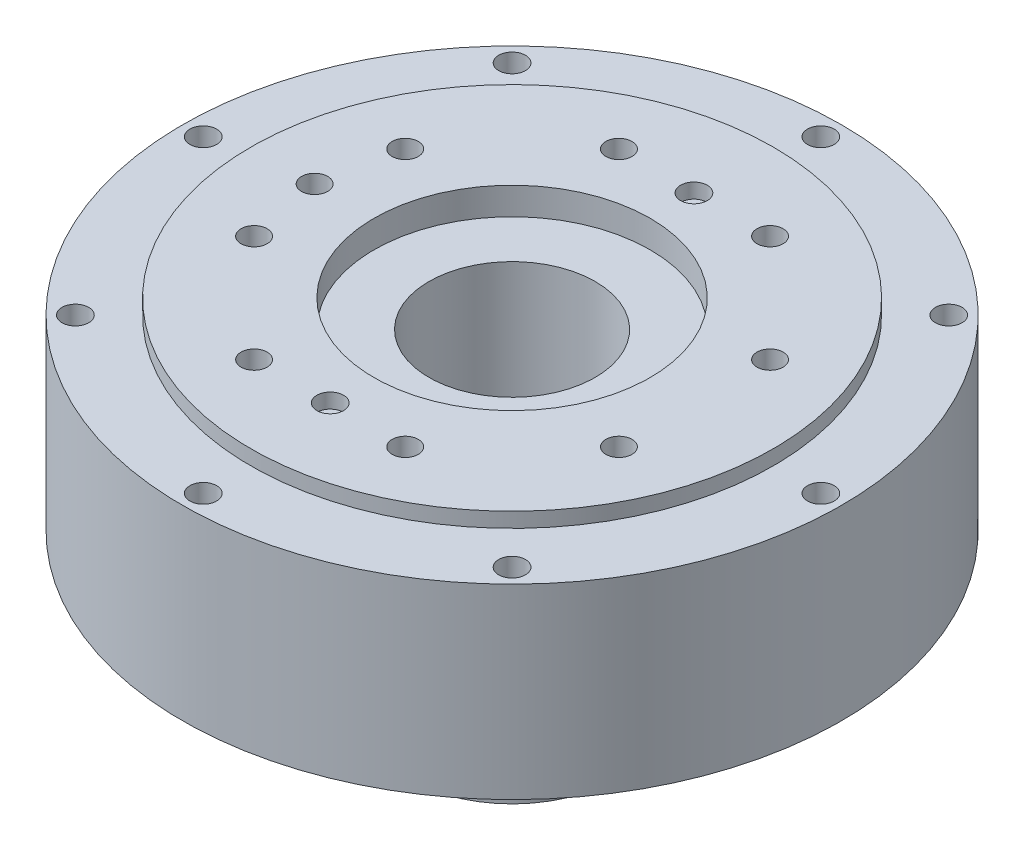
SolidWorks part; units mm, degrees
ref_plane "Front Plane" through (0, 0, 0) normal (0, 0, 1) x (1, 0, 0)
ref_plane "Top Plane" through (0, 0, 0) normal (0, 1, 0) x (1, 0, 0)
ref_plane "Right Plane" through (0, 0, 0) normal (1, 0, 0) x (0, 0, -1)
sketch "Sketch1" plane through (0, 0, 0) normal (1, 0, 0) x (0, 0, -1)
  line L4 (-28, 0) -> (-35, 0)
  line L5 (-35, 0) -> (-35, 34)
  line L12 (-35, 34) -> (-39.3, 34)
  line L13 (-39.3, 34) -> (-39.3, 44)
  line L14 (-39.3, 44) -> (-84.5, 44)
  line L15 (-84.5, 44) -> (-84.5, 55)
  line L20 (-84.5, 55) -> (-95, 55)
  line L23 (-111, 55) -> (-111, 117.85)
  line L24 (-111, 117.85) -> (-88, 117.85)
  line L25 (-88, 117.85) -> (-88, 122.85)
  line L26 (-88, 122.85) -> (-46.5, 122.85)
  line L28 (0, 0) -> (0, 248.8585) construction
  line L29 (-46.5, 122.85) -> (-46.5, 113.65)
  line L30 (-46.5, 113.65) -> (-28, 113.65)
  line L31 (0, 0) -> (-28, 0) construction
  line L32 (-28, 113.65) -> (-28, 0)
  line L33 (-98, 55) -> (-97.5, 57)
  line L34 (-97.5, 57) -> (-95.5, 57)
  line L35 (-95.5, 57) -> (-95, 55)
  line L36 (-96.5, 57) -> (-96.5, 55) construction
  line L37 (-95, 55) -> (-96.5, 56) construction
  line L38 (-96.5, 56) -> (-98, 55) construction
  line L39 (-98, 55) -> (-111, 55)
  dimension "D2" = 2
  dimension "D3" = 70
  dimension "D4" = 44
  dimension "D5" = 169
  dimension "D6" = 93
  dimension "D7" = 9.2
  dimension "D8" = 222
  dimension "D9" = 3
  dimension "D10" = 176
  dimension "D11" = 2
  dimension "D12" = 5
  dimension "D13" = 62.85
  dimension "D14" = 11
  dimension "D15" = 78.6
  dimension "D16" = 34
  dimension "D17" = 190
  dimension "D18" = 56
revolve "Revolve1" add sketch "Sketch1" angle 360 about L28
sketch "Sketch2" plane through (0, 117.85, 0) normal (0, 1, 0) x (1, 0, 0)
  line L0 (0, 0) -> (-178.8301, 0) construction
  circle A0 centre (0, 0) radius 104 construction
  circle A1 centre (-104, 0) radius 4.5
  circle A9 centre (-73.5391, 73.5391) radius 4.5
  circle A10 centre (0, 104) radius 4.5
  circle A11 centre (73.5391, 73.5391) radius 4.5
  circle A12 centre (104, 0) radius 4.5
  circle A13 centre (73.5391, -73.5391) radius 4.5
  circle A14 centre (0, -104) radius 4.5
  circle A15 centre (-73.5391, -73.5391) radius 4.5
  point P23 (0, 0)
  dimension "D1" = 9
  dimension "D4" = 208
  dimension "D2" = 8
extrude "Cut-Extrude1" cut sketch "Sketch2" against normal through all
sketch "Sketch4" plane through (0, 122.85, 0) normal (0, 1, 0) x (1, 0, 0)
  line L0 (0, 0) -> (-172.1172, 0) construction
  line L1 (0, 0) -> (-66.5, 0) construction
  line L2 (0, 0) -> (-61.438, 25.4484) construction
  circle A0 centre (0, 0) radius 66.5 construction
  circle A1 centre (-66.5, 0) radius 4.4
  circle A2 centre (-61.438, 25.4484) radius 4.4
  circle A4 centre (-25.4484, 61.438) radius 4.4
  circle A6 centre (25.4484, 61.438) radius 4.4
  circle A8 centre (61.438, 25.4484) radius 4.4
  circle A10 centre (61.438, -25.4484) radius 4.4
  circle A12 centre (25.4484, -61.438) radius 4.4
  circle A14 centre (-25.4484, -61.438) radius 4.4
  circle A16 centre (-61.438, -25.4484) radius 4.4
  circle A17 centre (-47.0226, 47.0226) radius 4.4 [skipped]
  circle A18 centre (-47.0226, -47.0226) radius 4.4 [skipped]
  circle A19 centre (0, -66.5) radius 4.4 [skipped]
  circle A20 centre (47.0226, -47.0226) radius 4.4 [skipped]
  circle A21 centre (66.5, 0) radius 4.4 [skipped]
  circle A22 centre (47.0226, 47.0226) radius 4.4 [skipped]
  circle A23 centre (0, 66.5) radius 4.4 [skipped]
  dimension "D1" = 133
  dimension "D2" = 8.8
  dimension "D3" = 16
  dimension "D4" = 22.5
extrude "Cut-Extrude3" cut sketch "Sketch4" against normal blind 18
sketch "Sketch5" plane through (0, 122.85, 0) normal (0, 1, 0) x (1, 0, 0)
  line L0 (0, 0) -> (0, -129.3283) construction
  circle A0 centre (0, 0) radius 61.25 construction
  circle A1 centre (0, -61.25) radius 4.5
  circle A3 centre (0, 61.25) radius 4.5
  circle A5 centre (-61.25, 0) radius 4.5 [skipped]
  circle A6 centre (61.25, 0) radius 4.5 [skipped]
  point P15 (0, 0)
  dimension "D1" = 122.5
  dimension "D2" = 9
  dimension "D3" = 4
extrude "Cut-Extrude4" cut sketch "Sketch5" against normal blind 5
sketch "Sketch6" plane through (0, 0, 0) normal (0, -1, 0) x (1, 0, 0)
  circle A0 centre (0, 0) radius 31.5 construction
  circle A1 centre (0, 31.5) radius 1.5
  circle A2 centre (27.2798, 15.75) radius 1.5
  circle A3 centre (27.2798, -15.75) radius 1.5
  circle A4 centre (0, -31.5) radius 1.5
  circle A5 centre (-27.2798, -15.75) radius 1.5
  circle A6 centre (-27.2798, 15.75) radius 1.5
  point P18 (0, 0)
  dimension "D1" = 63
  dimension "D2" = 3
  dimension "D3" = 6
extrude "Cut-Extrude5" cut sketch "Sketch6" against normal blind 8
